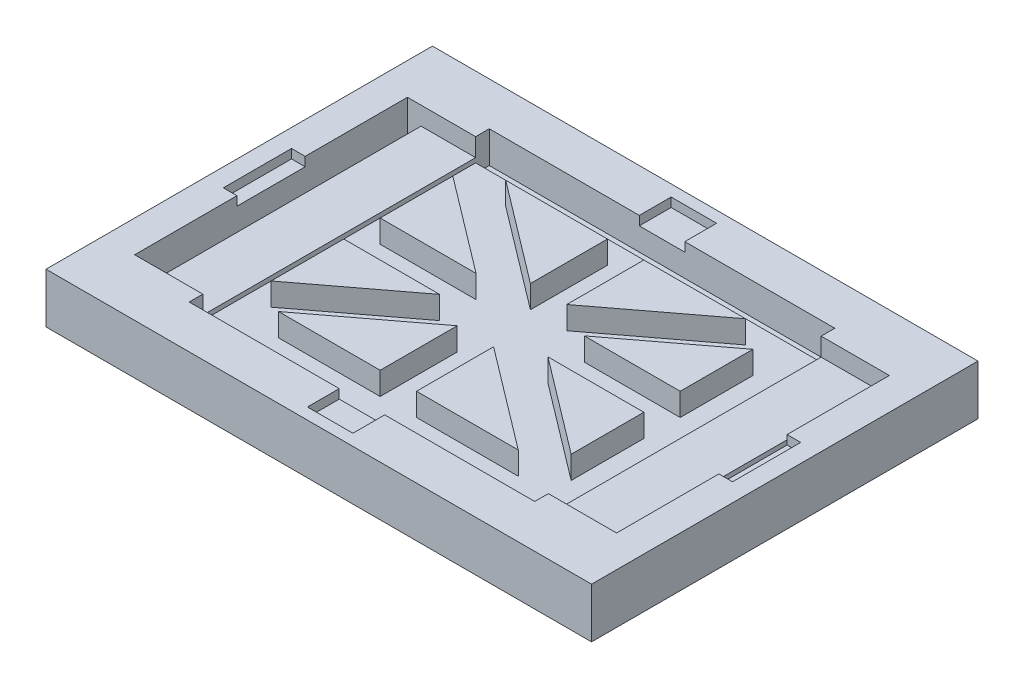
SolidWorks part; units mm, degrees
ref_plane "Front Plane" through (0, 0, 0) normal (0, 0, 1) x (1, 0, 0)
ref_plane "Top Plane" through (0, 0, 0) normal (0, 1, 0) x (1, 0, 0)
ref_plane "Right Plane" through (0, 0, 0) normal (1, 0, 0) x (0, 0, -1)
sketch "Sketch1" plane through (0, 0, 0) normal (0, 1, 0) x (1, 0, 0)
  line L1 (-53, -30) -> (53, -30)
  line L2 (-53, -30) -> (-53, 30)
  line L3 (-53, 30) -> (53, 30)
  line L4 (53, -30) -> (53, 30)
  line L5 (-53, -30) -> (53, 30) construction
  line L6 (-53, 30) -> (53, -30) construction
  line L7 (-56, -7.5) -> (56, -7.5)
  line L8 (-56, -7.5) -> (-56, 7.5)
  line L9 (-56, 7.5) -> (56, 7.5)
  line L10 (56, -7.5) -> (56, 7.5)
  line L11 (-56, -7.5) -> (56, 7.5) construction
  line L12 (-56, 7.5) -> (56, -7.5) construction
  line L13 (-5, -40) -> (5, -40)
  line L14 (-5, -40) -> (-5, 40)
  line L15 (-5, 40) -> (5, 40)
  line L16 (5, -40) -> (5, 40)
  line L17 (-5, -40) -> (5, 40) construction
  line L18 (-5, 40) -> (5, -40) construction
  line L19 (-60, -42.5) -> (60, -42.5)
  line L20 (-60, -42.5) -> (-60, 42.5)
  line L21 (-60, 42.5) -> (60, 42.5)
  line L22 (60, -42.5) -> (60, 42.5)
  line L23 (-60, -42.5) -> (60, 42.5) construction
  line L24 (-60, 42.5) -> (60, -42.5) construction
  line L25 (-50, 30) -> (-38, 30)
  line L26 (-50, 30) -> (-50, -30)
  line L27 (-50, -30) -> (-38, -30)
  line L28 (-38, 30) -> (-38, -30)
  line L29 (38, -30) -> (50, -30)
  line L30 (38, -30) -> (38, 30)
  line L31 (38, 30) -> (50, 30)
  line L32 (50, -30) -> (50, 30)
  line L33 (-53, 30) -> (-38, 30)
  line L34 (-53, 30) -> (-53, 25)
  line L35 (-53, 25) -> (-38, 25)
  line L36 (-38, 30) -> (-38, 25)
  line L37 (-38, 30) -> (38, 30)
  line L38 (-38, 30) -> (-38, 33)
  line L39 (-38, 33) -> (38, 33)
  line L40 (38, 30) -> (38, 33)
  line L41 (-38, -30) -> (38, -30)
  line L42 (-38, -30) -> (-38, -33)
  line L43 (-38, -33) -> (38, -33)
  line L44 (38, -30) -> (38, -33)
  point P0 (0, 0)
  point P6 (0, 0)
  point P11 (0, 0)
  point P16 (0, 0)
  dimension "D1" = 106
  dimension "D2" = 60
  dimension "D3" = 15
  dimension "D4" = 3
  dimension "D5" = 10
  dimension "D6" = 10
  dimension "D7" = 85
  dimension "D8" = 120
  dimension "D9" = 3
  dimension "D10" = 3
  dimension "D11" = 12
  dimension "D12" = 12
  dimension "D13" = 5
  dimension "D14" = 3
  dimension "D15" = 3
extrude "Boss-Extrude1" add sketch "Sketch1" along normal blind 15 contours L19 L22 L21 L20 L1 L44 L43 L16 L13 L14 L42 L2 L7 L8 L9 L3 L38 L39 L15 L40 L4 L10
sketch "Sketch9" plane through (0, 0, 0) normal (0, 1, 0) x (1, 0, 0)
  line L0 (-53, -30) -> (-38, -30) construction
  line L1 (-38, 30) -> (-50, 30)
  line L2 (-38, 30) -> (-38, -30)
  line L3 (-38, -30) -> (-50, -30)
  line L4 (-50, 30) -> (-50, -30)
  line L5 (38, -30) -> (53, -30) construction
  line L6 (38, 30) -> (50, 30)
  line L7 (38, 30) -> (38, -30)
  line L8 (38, -30) -> (50, -30)
  line L9 (50, 30) -> (50, -30)
  dimension "D1" = 12
  dimension "D2" = 12
extrude "Boss-Extrude2" add sketch "Sketch9" along normal blind 11 contours L2 L1 L4 L3 | L7 L6 L9 L8
sketch "Sketch10" plane through (0, 0, 0) normal (0, 1, 0) x (1, 0, 0)
  line L1 (-38, 30) -> (38, 30)
  line L2 (-38, 30) -> (-38, -30)
  line L3 (-38, -30) -> (38, -30)
  line L4 (38, 30) -> (38, -30)
extrude "Boss-Extrude4" add sketch "Sketch10" along normal blind 10
sketch "Sketch12" plane through (0, 0, 0) normal (0, 1, 0) x (1, 0, 0)
  line L0 (-53, -30) -> (-38, -30) construction
  line L1 (-53, 30) -> (-50, 30)
  line L2 (-53, 30) -> (-53, -30)
  line L3 (-53, -30) -> (-50, -30)
  line L4 (-50, 30) -> (-50, -30)
  line L5 (-50, 30) -> (-50, -30) construction
  line L7 (50, -30) -> (53, -30)
  line L8 (50, -30) -> (50, 30)
  line L9 (50, 30) -> (53, 30)
  line L10 (53, -30) -> (53, 30)
extrude "Boss-Extrude11" add sketch "Sketch12" along normal blind 6
sketch "Sketch13" plane through (0, 10, 0) normal (0, 1, 0) x (1, 0, 0)
  line L1 (-33, -25) -> (33, -25)
  line L2 (-33, -25) -> (-33, 25)
  line L3 (-33, 25) -> (33, 25)
  line L4 (33, -25) -> (33, 25)
  line L5 (-33, -25) -> (33, 25) construction
  line L6 (-33, 25) -> (33, -25) construction
  line L7 (38, 30) -> (-38, 30) construction
  line L8 (38, 30) -> (38, -30) construction
  line L9 (-35.4154, -21.8116) -> (30.5846, 28.1884)
  line L10 (-35.4154, -21.8116) -> (-30.5846, -28.1884)
  line L11 (30.5846, 28.1884) -> (35.4154, 21.8116)
  line L12 (-30.5846, -28.1884) -> (35.4154, 21.8116)
  line L13 (-35.4154, -21.8116) -> (35.4154, 21.8116) construction
  line L14 (30.5846, 28.1884) -> (-30.5846, -28.1884) construction
  line L15 (-35.4154, 21.8116) -> (30.5846, -28.1884)
  line L16 (-35.4154, 21.8116) -> (-30.5846, 28.1884)
  line L17 (30.5846, -28.1884) -> (35.4154, -21.8116)
  line L18 (-30.5846, 28.1884) -> (35.4154, -21.8116)
  line L19 (-35.4154, 21.8116) -> (35.4154, -21.8116) construction
  line L20 (30.5846, -28.1884) -> (-30.5846, 28.1884) construction
  line L22 (-33, -4) -> (33, -4)
  line L23 (-33, -4) -> (-33, 4)
  line L24 (-33, 4) -> (33, 4)
  line L25 (33, -4) -> (33, 4)
  line L26 (-33, -4) -> (33, 4) construction
  line L27 (-33, 4) -> (33, -4) construction
  line L28 (-4, -25) -> (4, -25)
  line L29 (-4, -25) -> (-4, 25)
  line L30 (-4, 25) -> (4, 25)
  line L31 (4, -25) -> (4, 25)
  line L32 (-4, -25) -> (4, 25) construction
  line L33 (-4, 25) -> (4, -25) construction
  point P0 (0, 0)
  point P10 (33, 25)
  point P11 (0, 0)
  point P12 (0, 0)
  point P17 (0, 0)
  point P26 (0, 0)
  dimension "D1" = 5
  dimension "D2" = 5
  dimension "D3" = 4
  dimension "D4" = 4
  dimension "D5" = 0
  dimension "D6" = 0
  dimension "D7" = 8
  dimension "D8" = 8
extrude "Boss-Extrude12" add sketch "Sketch13" along normal blind 5 contours L2 L24 L15 | L18 L29 L3 | L31 L9 L3 | L12 L24 L4 | L22 L18 L4 | L31 L1 L15 | L1 L29 L12 | L22 L2 L9
sketch "Sketch14" plane through (0, 0, 0) normal (0, 1, 0) x (1, 0, 0)
  line L1 (-38, 33) -> (38, 33)
  line L2 (-38, 33) -> (-38, 30)
  line L3 (-38, 30) -> (38, 30)
  line L4 (38, 33) -> (38, 30)
  line L5 (-38, -30) -> (38, -30)
  line L6 (-38, -30) -> (-38, -33)
  line L7 (-38, -33) -> (38, -33)
  line L8 (38, -30) -> (38, -33)
extrude "Boss-Extrude13" add sketch "Sketch14" along normal blind 8
sketch "Sketch15" plane through (0, 0, 0) normal (0, 1, 0) x (1, 0, 0)
  line L1 (-56, 7.5) -> (-53, 7.5)
  line L2 (-56, 7.5) -> (-56, -7.5)
  line L3 (-56, -7.5) -> (-53, -7.5)
  line L4 (-53, 7.5) -> (-53, -7.5)
  line L5 (-5, -33) -> (5, -33)
  line L6 (-5, -33) -> (-5, -40)
  line L7 (-5, -40) -> (5, -40)
  line L8 (5, -33) -> (5, -40)
  line L9 (53, -7.5) -> (56, -7.5)
  line L10 (53, -7.5) -> (53, 7.5)
  line L11 (53, 7.5) -> (56, 7.5)
  line L12 (56, -7.5) -> (56, 7.5)
  line L13 (-5, 33) -> (5, 33)
  line L14 (-5, 33) -> (-5, 40)
  line L15 (-5, 40) -> (5, 40)
  line L16 (5, 33) -> (5, 40)
extrude "Boss-Extrude14" add sketch "Sketch15" along normal blind 13
sketch "Sketch16" plane through (0, 0, 0) normal (0, -1, 0) x (1, 0, 0)
  line L4 (60, 42.5) -> (-60, 42.5)
  line L5 (-60, 42.5) -> (-60, -42.5)
  line L6 (-60, -42.5) -> (60, -42.5)
  line L7 (60, -42.5) -> (60, 42.5)
  line L8 (60, 42.5) -> (-60, 42.5)
  line L9 (-60, 42.5) -> (-60, -42.5)
  line L10 (-60, -42.5) -> (60, -42.5)
  line L11 (60, -42.5) -> (60, 42.5)
  dimension "D1" = 0
extrude "Cut-Extrude3" cut sketch "Sketch16" against normal blind 4
